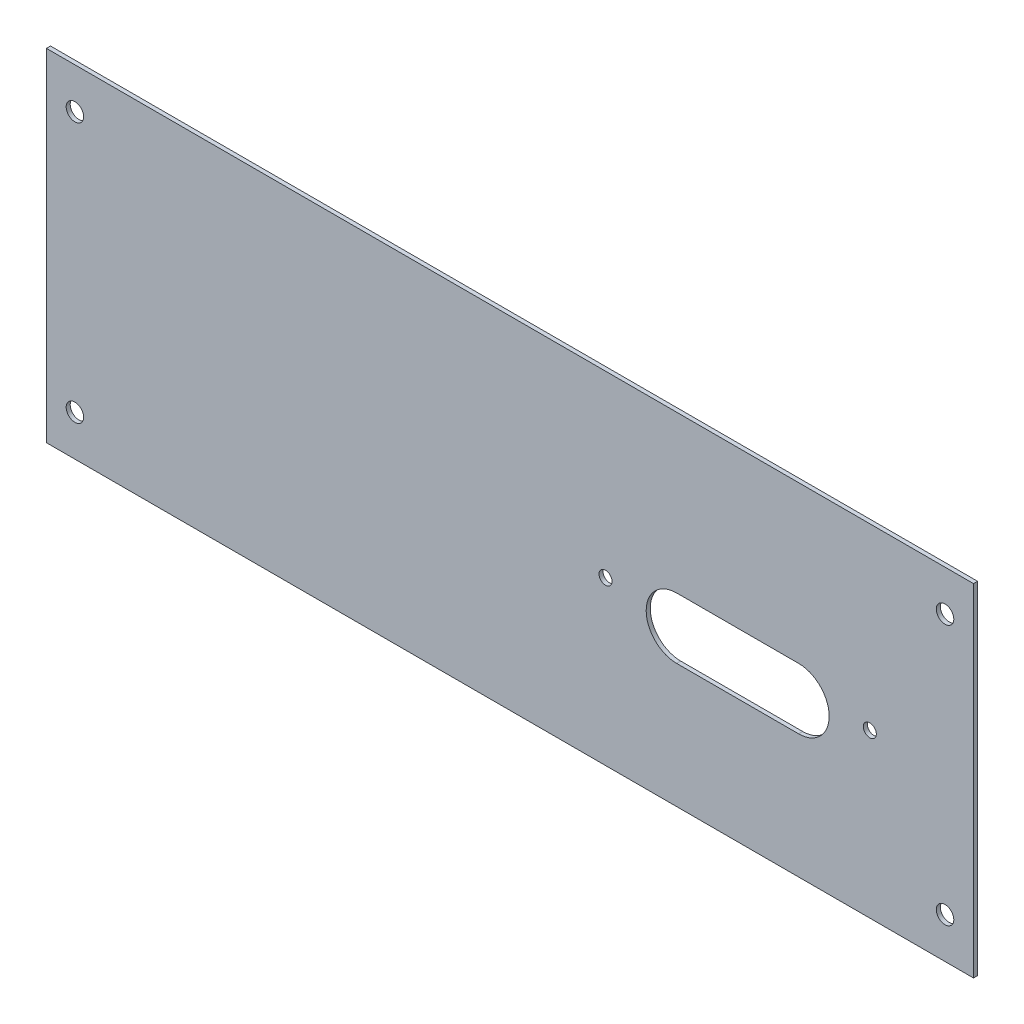
SolidWorks part; units mm, degrees
ref_plane "Спереди" through (0, 0, 0) normal (0, 0, 1) x (1, 0, 0)
ref_plane "Сверху" through (0, 0, 0) normal (0, 1, 0) x (1, 0, 0)
ref_plane "Справа" through (0, 0, 0) normal (1, 0, 0) x (0, 0, -1)
sketch "Эскиз1" plane through (0, 0, 0) normal (0, 0, 1) x (1, 0, 0)
  line L0 (0, 0) -> (58.061, 0) construction
  line L1 (0, 0) -> (0, 47.3035) construction
  line L2 (-15.7994, -2) -> (102.6804, -2) construction
  line L3 (-114, -42) -> (114, -42)
  line L4 (-114, -42) -> (-114, 42)
  line L5 (-114, 42) -> (114, 42)
  line L6 (114, -42) -> (114, 42)
  line L7 (18.7483, -4) -> (102.6804, -4) construction
  line L8 (41, 3.5) -> (71, 3.5)
  line L9 (41, -11.5) -> (71, -11.5)
  line L11 (56, 14.6924) -> (56, -15.7268) construction
  arc A0 (41, 3.5) -> (41, -11.5) centre (41, -4) ccw
  arc A1 (71, 3.5) -> (71, -11.5) centre (71, -4) cw
  circle A2 centre (23.5, -2) radius 1.6
  circle A8 centre (107, 32) radius 2.15
  circle A9 centre (-107, 32) radius 2.15
  circle A10 centre (-107, -32) radius 2.15
  circle A11 centre (107, -32) radius 2.15
  circle A12 centre (88.5, -2) radius 1.6
  dimension "D4" = 58
  dimension "D5" = 38
  dimension "D6" = 15
  dimension "D8" = 3.2
  dimension "D9" = 65
  dimension "D14" = 4.3
  dimension "D15" = 10
  dimension "D16" = 7
  dimension "D7" = 15
  dimension "D1" = 84
  dimension "D2" = 228
  dimension "D3" = 80
extrude "Вытянуть1" add sketch "Эскиз1" along normal blind 1
